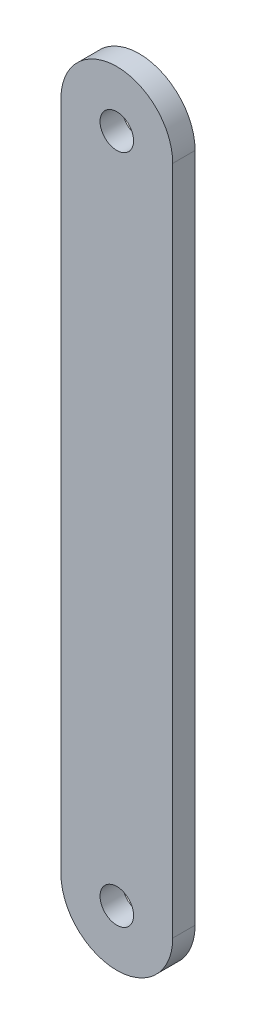
SolidWorks part; units mm, degrees
ref_plane "前视基准面" through (0, 0, 0) normal (0, 0, 1) x (1, 0, 0)
ref_plane "上视基准面" through (0, 0, 0) normal (0, 1, 0) x (1, 0, 0)
ref_plane "右视基准面" through (0, 0, 0) normal (1, 0, 0) x (0, 0, -1)
sketch "草图1" plane through (0, 0, 0) normal (0, 0, 1) x (1, 0, 0)
  line L0 (0, -30) -> (0, 30) construction
  line L1 (-5, -30) -> (-5, 30)
  line L2 (5, -30) -> (5, 30)
  line L3 (-1000, 0) -> (49000, 0) construction
  arc A0 (-5, -30) -> (5, -30) centre (0, -30) ccw
  arc A1 (5, 30) -> (-5, 30) centre (0, 30) ccw
  circle A2 centre (0, 30) radius 1.5
  circle A3 centre (0, -30) radius 1.5
  point P2 (0, 0)
  dimension "D3" = 3
  dimension "D1" = 60
  dimension "D2" = 10
extrude "凸台-拉伸1" add sketch "草图1" along normal blind 2
